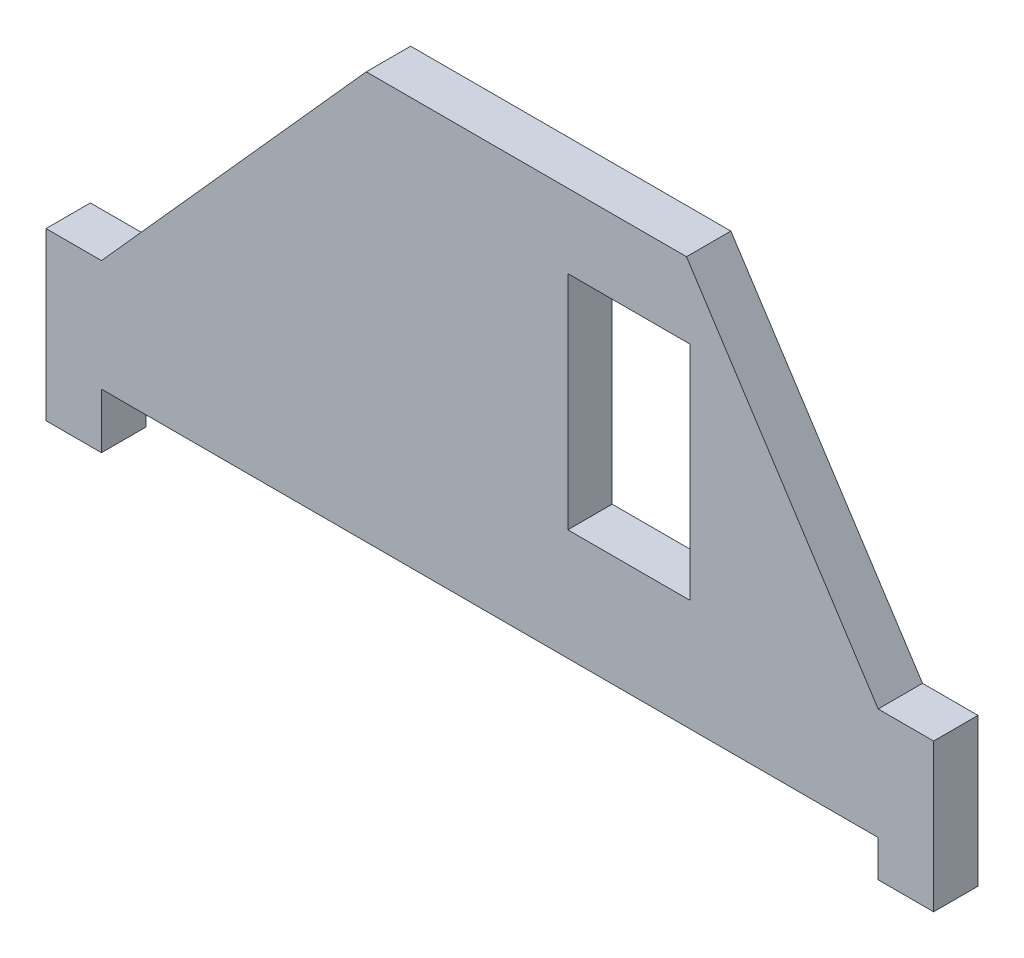
SolidWorks part; units mm, degrees
ref_plane "Front Plane" through (0, 0, 0) normal (0, 0, 1) x (1, 0, 0)
ref_plane "Top Plane" through (0, 0, 0) normal (0, 1, 0) x (1, 0, 0)
ref_plane "Right Plane" through (0, 0, 0) normal (1, 0, 0) x (0, 0, -1)
sketch "Sketch2" plane through (0, 0, 0) normal (0, 0, 1) x (1, 0, 0)
  line L0 (-127, 338.6667) -> (0, 338.6667)
  line L1 (-127, 0) -> (0, 0)
  line L2 (0, 0) -> (0, 338.6667)
  line L18 (-1905, -42.3333) -> (-2032, -42.3333)
  line L19 (-1905, 338.6667) -> (-2032, 338.6667)
  line L20 (-837.438, 338.6667) -> (-837.438, 846.6667)
  line L21 (-558.038, 846.6667) -> (-837.438, 846.6667)
  line L22 (-558.038, 338.6667) -> (-558.038, 846.6667)
  line L23 (-558.038, 338.6667) -> (-837.438, 338.6667)
  line L24 (-558.038, 338.6667) -> (-837.438, 338.6667)
  line L25 (-1905, 83.8002) -> (-1905, -42.3333)
  line L26 (-1905, -42.3333) -> (-1905, 83.8002)
  line L27 (-127, 83.8002) -> (-1905, 83.8002)
  line L28 (-127, 0) -> (-127, 83.8002)
  line L29 (-1298.8708, 1016) -> (-1905, 338.6667)
  line L30 (-127, 338.6667) -> (-565.7515, 1016)
  line L31 (-2032, -42.3333) -> (-2032, 338.6667)
  line L32 (-565.7515, 1016) -> (-1298.8708, 1016)
  dimension "D1" = 1067.562
  dimension "D2" = 381
  dimension "D3" = 338.6667
extrude "Boss-Extrude2" add sketch "Sketch2" along normal blind 101.6
